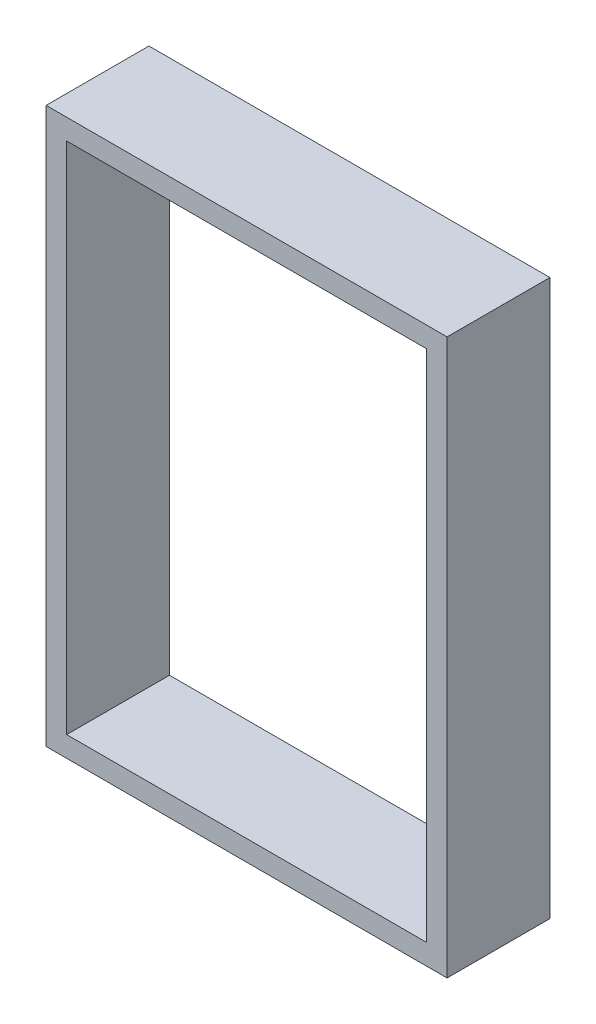
SolidWorks part; units mm, degrees
ref_plane "前视基准面" through (0, 0, 0) normal (0, 0, 1) x (1, 0, 0)
ref_plane "上视基准面" through (0, 0, 0) normal (0, 1, 0) x (1, 0, 0)
ref_plane "右视基准面" through (0, 0, 0) normal (1, 0, 0) x (0, 0, -1)
sketch "草图1" plane through (0, 0, 0) normal (0, 0, 1) x (1, 0, 0)
  line L1 (-1.75, 2.5) -> (1.75, 2.5)
  line L2 (-1.75, 2.5) -> (-1.75, -2.5)
  line L3 (-1.75, -2.5) -> (1.75, -2.5)
  line L4 (1.75, 2.5) -> (1.75, -2.5)
  line L5 (-1.75, 2.5) -> (1.75, -2.5) construction
  line L6 (-1.75, -2.5) -> (1.75, 2.5) construction
  line L7 (-1.95, 2.7) -> (1.95, 2.7)
  line L8 (-1.95, 2.7) -> (-1.95, -2.7)
  line L9 (-1.95, -2.7) -> (1.95, -2.7)
  line L10 (1.95, 2.7) -> (1.95, -2.7)
  line L11 (-1.95, 2.7) -> (1.95, -2.7) construction
  line L12 (-1.95, -2.7) -> (1.95, 2.7) construction
  point P0 (0, 0)
  point P6 (0, 0)
  dimension "D1" = 3.5
  dimension "D2" = 5
  dimension "D3" = 0.2
  dimension "D4" = 0.2
extrude "凸台-拉伸1" add sketch "草图1" along normal blind 1
